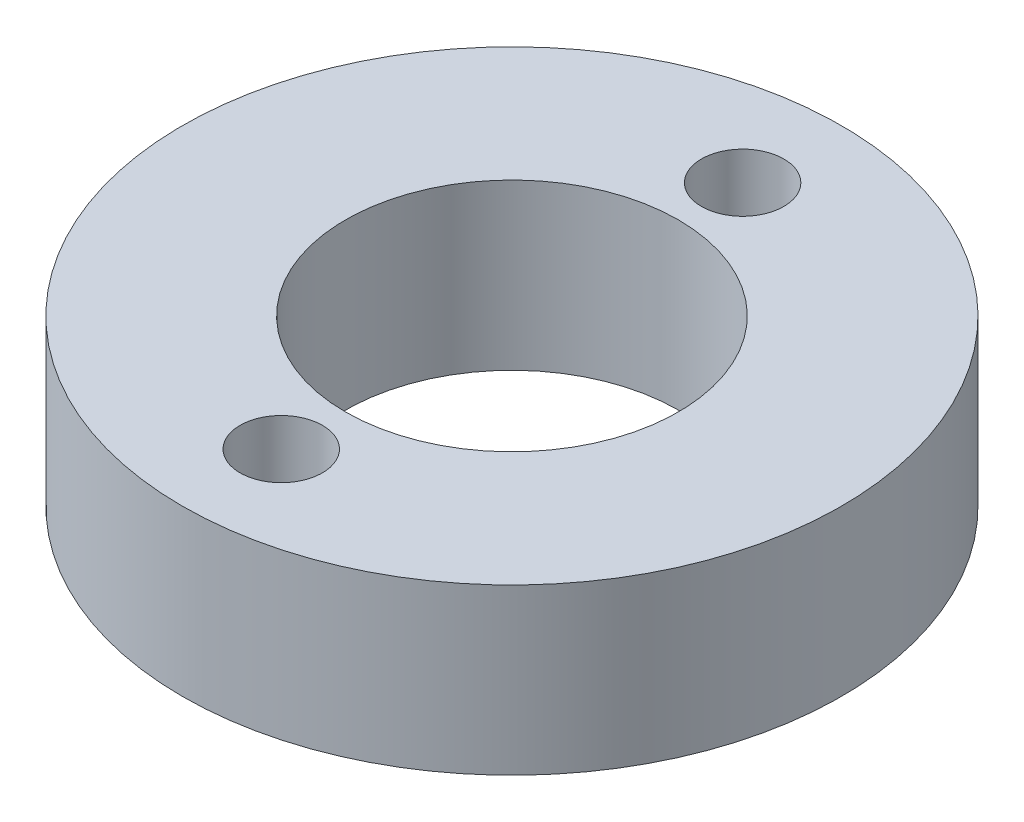
SolidWorks part; units mm, degrees
material "6061-T6 (SS)"
ref_plane "Front Plane" through (0, 0, 0) normal (0, 0, 1) x (1, 0, 0)
ref_plane "Top Plane" through (0, 0, 0) normal (0, 1, 0) x (1, 0, 0)
ref_plane "Right Plane" through (0, 0, 0) normal (1, 0, 0) x (0, 0, -1)
sketch "Sketch1" plane through (0, 0, 0) normal (0, 1, 0) x (1, 0, 0)
  circle A0 centre (0, 0) radius 10
  circle A1 centre (0, 0) radius 5.05
  dimension "D1" = 20
  dimension "D2" = 10.1
extrude "Boss-Extrude1" add sketch "Sketch1" along normal blind 5
cosmetic thread "Cosmetic Thread1" parameters "D2"=17.252
sketch "Sketch2" plane through (0, 5, 0) normal (0, 1, 0) x (1, 0, 0)
  circle A0 centre (0, 7) radius 1.25
  dimension "D1" = 2.5
  dimension "D2" = 7
extrude "Cut-Extrude1" cut sketch "Sketch2" against normal blind 2.5
pattern_circular "CirPattern1" count 2 over 360 about axis through (0, 0, 0) along (0, 1, 0) of "Cut-Extrude1"
